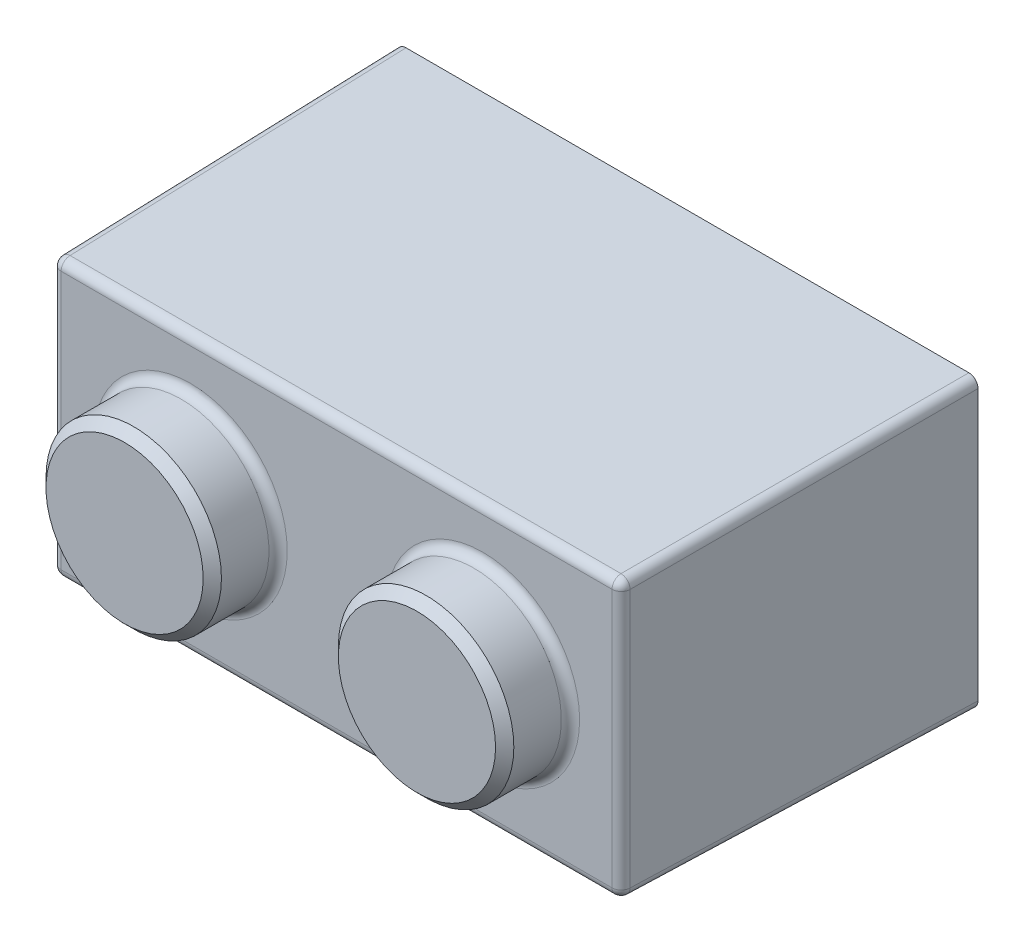
SolidWorks part; units mm, degrees
material "ABS"
ref_plane "Front" through (0, 0, 0) normal (0, 0, 1) x (1, 0, 0)
ref_plane "Top" through (0, 0, 0) normal (0, 1, 0) x (1, 0, 0)
ref_plane "Right" through (0, 0, 0) normal (1, 0, 0) x (0, 0, -1)
sketch "Sketch1" plane through (0, 0, 0) normal (0, 0, 1) x (1, 0, 0)
  line L1 (0, 0) -> (15.9, 0)
  line L2 (0, 0) -> (0, 7.9)
  line L3 (0, 7.9) -> (15.9, 7.9)
  line L4 (15.9, 0) -> (15.9, 7.9)
  dimension "D1" = 15.9
  dimension "D2" = 7.9
extrude "Main Body" add sketch "Sketch1" along normal blind 9.6 draft 1
sketch "Sketch2" plane through (0, 0, 9.6) normal (0, 0, 1) x (1, 0, 0)
  line L1 (0, 7.9) -> (0, 0) construction
  line L2 (0, 0) -> (15.9, 0) construction
  circle A0 centre (3.95, 3.95) radius 2.4
  dimension "D3" = 4.8
  dimension "D1" = 3.95
  dimension "D2" = 3.95
extrude "Post" add sketch "Sketch2" along normal blind 1.8
pattern_linear "Post LPattern1" count 2 spacing 8 along (1, 0, 0) of "Post"
shell "Shell1" thickness 1.2
fillet "Body Fillet" radius 0.25 10 edges at (7.95, 7.7324, 9.6) (15.7324, 3.95, 9.6) (7.95, 0.1676, 9.6) (0.1676, 3.95, 9.6) (1.55, 3.95, 9.6) (9.55, 3.95, 9.6) (15.8162, 7.8162, 4.8) (15.8162, 0.0838, 4.8) (0.0838, 7.8162, 4.8) (0.0838, 0.0838, 4.8)
chamfer "Post Chamfer" distance 0.25 angle 45 2 edges at (6.35, 3.95, 11.4) (14.35, 3.95, 11.4)
sketch "Sketch3" [suppressed] plane through (0, 0, 0) normal (0, 1, 0) x (1, 0, 0)
  line L1 (0, 0) -> (0.1633, -9.3544) construction
  line L3 (15.9563, -1.5437) -> (15.9563, -11.4)
  line L4 (0, 0) -> (0.1633, -9.3544) construction
  line L5 (0, 0) -> (0, -11.4) construction
  line L6 (0, -11.4) -> (7.9, -11.4) construction
  line L8 (7.9, -11.4) -> (15.9563, -11.4)
  line L9 (0.4132, -9.6) -> (15.4868, -9.6) construction
  line L10 (7.9, -9.6) -> (15.9563, -9.6) construction
  line L11 (7.9, -11.4) -> (7.9, -9.6)
  line L12 (7.9, -9.6) -> (15.9563, -1.5437)
  dimension "D1" = 11.4
  dimension "D2" = 7.9
  dimension "D3" = 45
extrude "Cut-Extrude1" [suppressed] cut sketch "Sketch3" along normal up to surface (7.7324 mm away)
sketch "Sketch4" [suppressed] plane through (8.75, 0, 8.75) normal (0.7071, 0, 0.7071) x (0.7071, 0, -0.7071)
  line L4 (-0.8547, 0.1633) -> (9.7116, 0.0329)
  line L5 (10.0714, 0.2784) -> (10.0714, 7.6216)
  line L6 (9.7116, 7.8671) -> (-0.8547, 7.7367)
  line L7 (-1.2021, 7.4868) -> (-1.2021, 0.4132)
  line L8 (-0.8547, 0.1633) -> (9.7116, 0.0329)
  line L9 (10.0714, 0.2784) -> (10.0714, 7.6216)
  line L10 (9.7116, 7.8671) -> (-0.8547, 7.7367)
  line L11 (-1.2021, 7.4868) -> (-1.2021, 0.4132)
  ellipse E4 centre (9.7115, 0.2829) end of major axis (10.0714, 0.2742) minor radius 0.25 (9.7116, 0.0329) -> (10.0714, 0.2784) ccw
  ellipse E5 centre (9.7115, 7.6171) end of major axis (10.0714, 7.6258) minor radius 0.25 (10.0714, 7.6216) -> (9.7116, 7.8671) ccw
  ellipse E6 centre (-0.8485, 7.4868) end of major axis (-0.495, 7.4868) minor radius 0.25 (-0.8547, 7.7367) -> (-1.2021, 7.4868) ccw
  ellipse E7 centre (-0.8485, 0.4132) end of major axis (-1.2021, 0.4132) minor radius 0.25 (-1.2021, 0.4132) -> (-0.8547, 0.1633) ccw
  ellipse E8 centre (9.7115, 0.2829) end of major axis (10.0714, 0.2742) minor radius 0.25 (9.7116, 0.0329) -> (10.0714, 0.2784) ccw
  ellipse E9 centre (9.7115, 7.6171) end of major axis (10.0714, 7.6258) minor radius 0.25 (10.0714, 7.6216) -> (9.7116, 7.8671) ccw
  ellipse E10 centre (-0.8485, 7.4868) end of major axis (-0.495, 7.4868) minor radius 0.25 (-0.8547, 7.7367) -> (-1.2021, 7.4868) ccw
  ellipse E11 centre (-0.8485, 0.4132) end of major axis (-1.2021, 0.4132) minor radius 0.25 (-1.2021, 0.4132) -> (-0.8547, 0.1633) ccw
  dimension "D1" = 0
extrude "Boss-Extrude1" [suppressed] add sketch "Sketch4" against normal blind 1.2
fillet "Fillet1" [suppressed] radius 0.25
